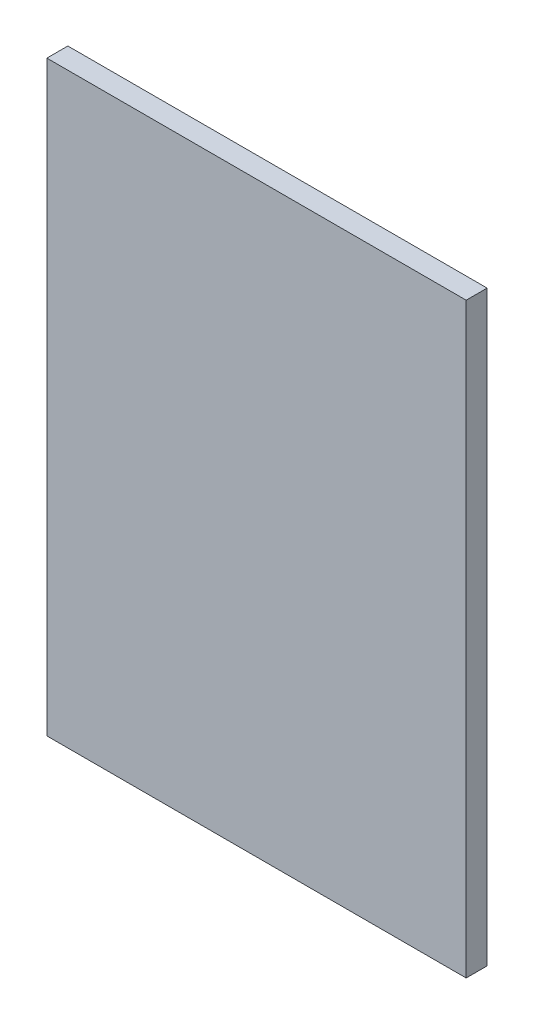
SolidWorks part; units mm, degrees
material "Oak"
ref_plane "Front Plane" through (0, 0, 0) normal (0, 0, 1) x (1, 0, 0)
ref_plane "Top Plane" through (0, 0, 0) normal (0, 1, 0) x (1, 0, 0)
ref_plane "Right Plane" through (0, 0, 0) normal (1, 0, 0) x (0, 0, -1)
sketch "Sketch1" plane through (0, 0, 0) normal (0, 0, 1) x (1, 0, 0)
  line L1 (-25, 35) -> (25, 35)
  line L2 (-25, 35) -> (-25, -35)
  line L3 (-25, -35) -> (25, -35)
  line L4 (25, 35) -> (25, -35)
  line L5 (-25, 35) -> (25, -35) construction
  line L6 (-25, -35) -> (25, 35) construction
  point P0 (0, 0)
  dimension "D1" = 70
  dimension "D2" = 50
extrude "Boss-Extrude1" add sketch "Sketch1" along normal blind 2.5
